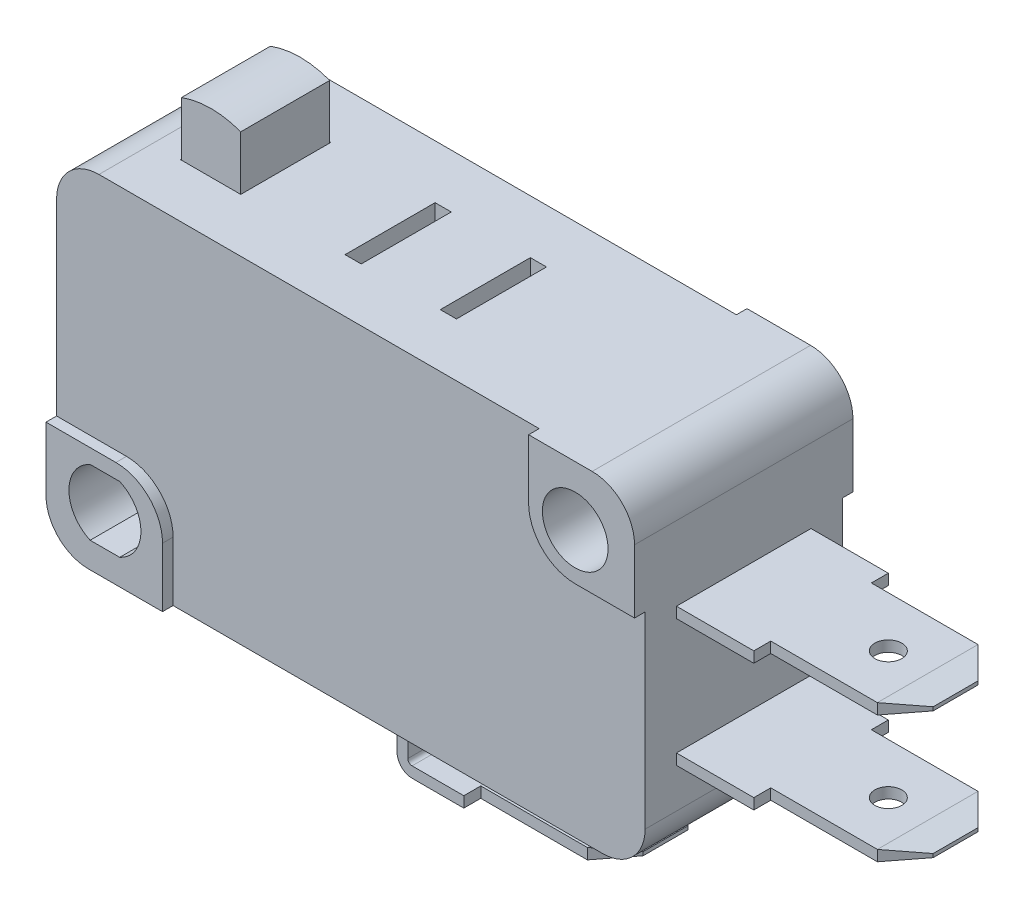
SolidWorks part; units mm, degrees
ref_plane "Front" through (0, 0, 0) normal (0, 0, 1) x (1, 0, 0)
ref_plane "Top" through (0, 0, 0) normal (0, 1, 0) x (1, 0, 0)
ref_plane "Right" through (0, 0, 0) normal (1, 0, 0) x (0, 0, -1)
sketch "Sketch1" plane through (0, 0, 0) normal (0, 0, 1) x (1, 0, 0)
  line L0 (-13.8906, -7.9375) -> (13.8906, 7.9375) construction
  line L1 (-13.8906, 7.9375) -> (13.8906, 7.9375)
  line L2 (-13.8906, 7.9375) -> (-13.8906, -7.9375)
  line L3 (-13.8906, -7.9375) -> (13.8906, -7.9375)
  line L4 (13.8906, 7.9375) -> (13.8906, -7.9375)
  line L5 (-11.8076, -3.6253) -> (-10.4112, -3.6253)
  line L6 (-9.4094, -5.1753) -> (-12.8094, -5.1753) construction
  line L7 (-10.4112, -6.7253) -> (-11.8076, -6.7253)
  circle A0 centre (11.0906, 5.1435) radius 1.55
  arc A1 (-11.8076, -3.6253) -> (-11.8076, -6.7253) centre (-11.1094, -5.1753) ccw
  arc A2 (-10.4112, -6.7253) -> (-10.4112, -3.6253) centre (-11.1094, -5.1753) ccw
  dimension "D3" = 3.1
  dimension "D5" = 3.4
  dimension "D7" = 22.2
  dimension "D8" = 10.3187
  dimension "D9" = 2.794
  dimension "D6" = 2.8
  dimension "D1" = 27.7812
  dimension "D2" = 15.875
  dimension "D4" = 3.1
extrude "Extrude1" add sketch "Sketch1" along normal mid plane 10.31
fillet "Fillet1" radius 2 4 edges at (-13.8906, -7.9375, 0) (13.8906, -7.9375, 0) (-13.8906, 7.9375, 0) (13.8906, 7.9375, 0)
sketch "Sketch2" plane through (0, 0, 0) normal (0, 0, 1) x (1, 0, 0)
  line L0 (-10.5532, 7.4717) -> (-10.5532, 10.4717)
  line L1 (-9.1532, 6.7247) -> (-9.1532, 7.4717) construction
  line L2 (-7.7532, 10.4717) -> (-7.7532, 7.4717)
  line L3 (-7.7532, 7.4717) -> (-10.5532, 7.4717)
  arc A0 (-10.5532, 10.4717) -> (-7.7532, 10.4717) centre (-9.1532, 6.7247) cw
  circle A2 centre (11.0906, 5.1435) radius 1.55 construction
  arc A3 (-11.8076, -3.6253) -> (-11.8076, -6.7253) centre (-11.1094, -5.1753) ccw construction
  point P5 (-9.1532, 9.5247)
  dimension "D1" = 14.7
  dimension "D3" = 20.2438
  dimension "D4" = 4
  dimension "D2" = 2.8
  dimension "D5" = 3
  dimension "D6" = 1.2
extrude "Extrude2" add sketch "Sketch2" along normal mid plane 4.2 separate body
sketch "Sketch3" plane through (0, 7.9375, 0) normal (0, 1, 0) x (-1, 0, 0)
  line L0 (10.5532, 2.1) -> (10.5532, -2.1) construction
  line L1 (7.7278, 2.1254) -> (7.7278, -2.1254)
  line L2 (7.7278, -2.1254) -> (10.5786, -2.1254)
  line L3 (10.5786, 2.1254) -> (10.5786, -2.1254)
  line L4 (10.5786, 2.1254) -> (7.7278, 2.1254)
  line L5 (10.5532, 2.1) -> (7.7532, 2.1) construction
  line L6 (7.7532, -2.1) -> (10.5532, -2.1) construction
  line L7 (7.7532, 2.1) -> (7.7532, -2.1) construction
  line L8 (10.5532, 2.1) -> (10.5532, -2.1) construction
  line L9 (10.5532, 2.1) -> (7.7532, 2.1) construction
  line L10 (7.7532, -2.1) -> (10.5532, -2.1) construction
  line L11 (7.7532, 2.1) -> (7.7532, -2.1) construction
  line L12 (2.4222, 2.1254) -> (2.4222, -2.1254) construction
  line L13 (2.8032, 2.1254) -> (2.0412, 2.1254)
  line L14 (2.8032, 2.1254) -> (2.8032, -2.1254)
  line L15 (2.8032, -2.1254) -> (2.0412, -2.1254)
  line L16 (2.0412, 2.1254) -> (2.0412, -2.1254)
  line L17 (-1.6926, 2.1254) -> (-2.4546, 2.1254)
  line L18 (-1.6926, 2.1254) -> (-1.6926, -2.1254)
  line L19 (-1.6926, -2.1254) -> (-2.4546, -2.1254)
  line L20 (-2.4546, 2.1254) -> (-2.4546, -2.1254)
  line L21 (-2.0736, -2.1254) -> (-2.0736, 2.1254) construction
  dimension "D2" = 9.017
  dimension "D3" = 4.4958
  dimension "D4" = 0.762
  dimension "D1" = 0.0254
extrude "Cut-Extrude1" cut sketch "Sketch3" against normal blind 2
sketch "Sketch4" plane through (0, 0, 5.155) normal (0, 0, 1) x (1, 0, 0)
  line L0 (-10.4112, -6.7253) -> (-11.8076, -6.7252) construction
  line L1 (-11.8076, -3.6253) -> (-10.4112, -3.6253) construction
  line L2 (-13.8906, -7.9375) -> (13.8906, -7.9375) construction
  line L3 (13.8906, 7.9375) -> (13.8906, -7.9375) construction
  line L4 (-13.8906, 7.9375) -> (13.8906, 7.9375) construction
  line L5 (-13.8906, 7.9375) -> (-13.8906, -7.9375) construction
  line L6 (-10.4112, -6.7253) -> (-11.8076, -6.7252) construction
  line L7 (-11.8076, -3.6253) -> (-10.4112, -3.6253) construction
  line L8 (-8.3906, -7.9375) -> (13.8906, -7.9375)
  line L9 (13.8906, 2.9435) -> (13.8906, -7.9375)
  line L10 (-13.8906, 7.9375) -> (8.8906, 7.9375)
  line L11 (-13.8906, 7.9375) -> (-13.8906, -2.9375)
  line L12 (-13.8906, -2.9375) -> (-10.5906, -2.9375)
  line L13 (-8.3906, -5.1375) -> (-8.3906, -7.9375)
  line L14 (8.8906, 7.9375) -> (8.8906, 5.1435)
  line L15 (11.0906, 2.9435) -> (13.8906, 2.9435)
  arc A0 (-11.8076, -3.6253) -> (-11.8076, -6.7252) centre (-11.1094, -5.1753) ccw construction
  arc A1 (-10.4112, -6.7253) -> (-10.4112, -3.6253) centre (-11.1094, -5.1753) ccw construction
  circle A2 centre (11.0906, 5.1435) radius 1.55 construction
  arc A3 (-11.8076, -3.6253) -> (-11.8076, -6.7252) centre (-11.1094, -5.1753) ccw construction
  arc A4 (-10.4112, -6.7253) -> (-10.4112, -3.6253) centre (-11.1094, -5.1753) ccw construction
  circle A5 centre (11.0906, 5.1435) radius 1.55 construction
  arc A6 (-10.5906, -2.9375) -> (-8.3906, -5.1375) centre (-10.5906, -5.1375) cw
  arc A7 (8.8906, 5.1435) -> (11.0906, 2.9435) centre (11.0906, 5.1435) ccw
  dimension "D1" = 5
  dimension "D2" = 5.5
  dimension "D3" = 5
extrude "Cut-Extrude2" cut sketch "Sketch4" against normal blind 0.5
mirror "Mirror1" about plane through (0, 0, 0) normal (0, 0, 1) of "Cut-Extrude2"
sketch "Sketch5" plane through (0, 0, 0) normal (0, 0, 1) x (1, 0, 0)
  line L0 (0.7016, -7.9375) -> (0.7016, -10.1295)
  line L1 (-13.8906, -7.9375) -> (13.8906, -7.9375) construction
  line L2 (1.4096, -10.8375) -> (10.2016, -10.8375)
  line L3 (10.2016, -10.8375) -> (10.2016, -10.3295)
  line L4 (10.2016, -10.3295) -> (1.4096, -10.3295)
  line L5 (1.2096, -10.1295) -> (1.2096, -7.9375)
  line L6 (1.2096, -7.9375) -> (0.7016, -7.9375)
  line L7 (-13.8906, 7.9375) -> (13.8906, 7.9375) construction
  line L8 (-8.3906, -7.9375) -> (11.8906, -7.9375) construction
  arc A0 (0.7016, -10.1295) -> (1.4096, -10.8375) centre (1.4096, -10.1295) ccw
  arc A1 (1.4096, -10.3295) -> (1.2096, -10.1295) centre (1.4096, -10.1295) cw
  arc A2 (-10.4112, -6.7253) -> (-10.4112, -3.6253) centre (-11.1094, -5.1753) ccw construction
  circle A3 centre (11.0906, 5.1435) radius 1.55 construction
  dimension "D1" = 11.811
  dimension "D4" = 0.889
  dimension "D5" = 0.2
  dimension "D2" = 2.392
  dimension "D3" = 0.508
  dimension "D6" = 18.775
  dimension "D7" = 2.9
extrude "Extrude3" add sketch "Sketch5" along normal mid plane 6.35
sketch "Sketch6" plane through (0, -10.3295, 0) normal (0, 1, 0) x (-1, 0, 0)
  line L0 (11.873, 0) -> (-11.873, 0) construction
  line L1 (-10.2016, 3.175) -> (-10.2016, -3.175) construction
  line L2 (-10.2016, 1.0583) -> (-8.8851, 2.3749)
  line L3 (-8.8851, 2.3749) -> (-3.8516, 2.3749)
  line L4 (-3.8516, 2.3749) -> (-3.8516, 3.175)
  line L5 (-3.8516, 3.175) -> (-10.2016, 3.175)
  line L6 (-10.2016, 3.175) -> (-10.2016, 1.0583)
  line L7 (-7.0266, 0) -> (-10.2016, 0) construction
  line L8 (-10.2016, -3.175) -> (-10.2016, -1.0583)
  line L9 (-3.8516, -3.175) -> (-10.2016, -3.175)
  line L10 (-3.8516, -2.3749) -> (-3.8516, -3.175)
  line L11 (-8.8851, -2.3749) -> (-3.8516, -2.3749)
  line L12 (-10.2016, -1.0583) -> (-8.8851, -2.3749)
  line L13 (-10.2016, 3.175) -> (-1.4096, 3.175) construction
  line L14 (-10.2016, 1.0583) -> (-10.2016, -1.0583) construction
  circle A0 centre (-7.0266, 0) radius 0.635
  dimension "D1" = 1.27
  dimension "D2" = 3.175
  dimension "D3" = 4.7498
  dimension "D4" = 45
  dimension "D5" = 6.35
extrude "Cut-Extrude3" cut sketch "Sketch6" against normal through all
sketch "Sketch8" plane through (0, 7.9375, 0) normal (0, 1, 0) x (-1, 0, 0)
  line L0 (-13.8906, -3.175) -> (-17.5406, -3.175)
  line L1 (-17.5406, -3.175) -> (-17.5406, -2.3749)
  line L2 (-17.5406, -2.3749) -> (-22.5741, -2.3749)
  line L3 (-22.5741, -2.3749) -> (-23.8906, -1.0583)
  line L4 (-23.8906, -1.0583) -> (-23.8906, 1.0583)
  line L5 (-23.8906, 1.0583) -> (-22.5741, 2.3749)
  line L6 (-22.5741, 2.3749) -> (-17.5406, 2.3749)
  line L7 (-17.5406, 2.3749) -> (-17.5406, 3.175)
  line L8 (-17.5406, 3.175) -> (-13.8906, 3.175)
  line L9 (-13.8906, 3.175) -> (-13.8906, -3.175)
  line L10 (-23.8906, 0) -> (-13.8906, 0) construction
  line L11 (-17.5406, -3.175) -> (-23.8906, -3.175) construction
  line L12 (-23.8906, -3.175) -> (-23.8906, -1.0583) construction
  line L13 (-23.8906, 1.0583) -> (-23.8906, 3.175) construction
  line L14 (-23.8906, 3.175) -> (-17.5406, 3.175) construction
  line L15 (-13.8906, 4.655) -> (-13.8906, -4.655) construction
  circle A0 centre (-20.7156, 0) radius 0.635
  point P14 (-13.8906, 0)
  dimension "D3" = 1.27
  dimension "D1" = 4.7498
  dimension "D2" = 6.35
  dimension "D4" = 3.175
  dimension "D5" = 6.35
  dimension "D6" = 10
extrude "Extrude4" add sketch "Sketch8" against normal blind 0.508 from offset 5.5 offset against normal yes
pattern_linear "LPattern1" count 2 spacing 6 along (0, -1, 0) of "Extrude4"
sketch "Sketch7" plane through (0, 0, 0) normal (0, 0, 1) x (1, 0, 0)
  line L0 (8.8851, -10.3295) -> (10.2016, -10.3295)
  line L1 (10.2016, -10.3295) -> (10.2016, -10.4988)
  line L2 (10.2016, -10.4988) -> (8.8851, -10.3295)
  line L3 (8.8851, -10.8375) -> (10.2016, -10.8375)
  line L4 (10.2016, -10.8375) -> (10.2016, -10.6682)
  line L5 (10.2016, -10.6682) -> (8.8851, -10.8375)
  line L6 (10.2016, -10.3295) -> (1.4096, -10.3295) construction
  line L7 (1.4096, -10.8375) -> (10.2016, -10.8375) construction
  line L8 (8.8851, -10.3295) -> (8.8851, -10.8375) construction
  line L9 (10.2016, -10.8375) -> (10.2016, -10.3295) construction
  line L10 (10.2016, -10.4988) -> (10.2016, -10.6682) construction
  line L11 (22.5741, 2.4375) -> (23.8906, 2.2682)
  line L12 (23.8906, 1.9295) -> (23.8906, 2.4375) construction
  line L13 (23.8906, 2.2682) -> (23.8906, 2.4375)
  line L14 (23.8906, 2.4375) -> (22.5741, 2.4375)
  line L15 (22.5741, 1.9295) -> (23.8906, 1.9295)
  line L16 (23.8906, 1.9295) -> (23.8906, 2.0988)
  line L17 (23.8906, 2.0988) -> (22.5741, 1.9295)
  line L18 (23.8906, 2.2682) -> (23.8906, 2.0988) construction
  line L20 (23.8906, -3.5625) -> (23.8906, -3.7318)
  line L21 (23.8906, -4.0705) -> (23.8906, -3.5625) construction
  line L22 (23.8906, -3.7318) -> (23.8906, -3.9012) construction
  line L23 (23.8906, -3.9012) -> (23.8906, -4.0705)
  line L24 (22.5741, -4.0705) -> (23.8906, -4.0705) construction
  line L25 (23.8906, -4.0705) -> (22.5741, -4.0705)
  line L26 (22.5741, -4.0705) -> (23.8906, -3.9012)
  line L27 (23.8906, -3.7318) -> (22.5741, -3.5625)
  line L28 (22.5741, -3.5625) -> (23.8906, -3.5625)
extrude "Cut-Extrude4" cut sketch "Sketch7" against normal through all and the other way through all
sketch "Sketch9" plane through (0, 0, 0) normal (0, 0, 1) x (1, 0, 0)
  line L0 (-9.1532, 10.7248) -> (-9.1532, 9.5248) construction
  arc A2 (-7.7532, 10.4717) -> (-10.5532, 10.4717) centre (-9.1532, 6.7247) ccw construction
  point P5 (-9.1532, 9.8247)
  point P6 (-9.1532, 9.4248)
  dimension "D1" = 0.3
  dimension "D2" = 0.1
  dimension "D3" = 1.2
